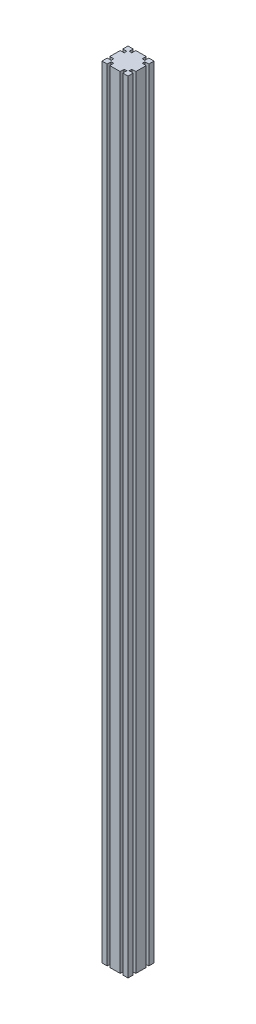
SolidWorks part; units mm, degrees
ref_plane "Front Plane" through (0, 0, 0) normal (0, 0, 1) x (1, 0, 0)
ref_plane "Top Plane" through (0, 0, 0) normal (0, 1, 0) x (1, 0, 0)
ref_plane "Right Plane" through (0, 0, 0) normal (1, 0, 0) x (0, 0, -1)
sketch "Sketch1" plane through (0, 0, 0) normal (0, 1, 0) x (1, 0, 0)
  line L0 (56.6792, 50.48) -> (48.6792, 50.48)
  line L1 (-7.3208, 50.48) -> (8.6792, 50.48)
  line L2 (16.6792, 50.48) -> (48.6792, 50.48)
  line L3 (56.6792, 50.48) -> (72.6792, 50.48)
  line L4 (8.6792, 50.48) -> (16.6792, 50.48)
  line L5 (8.6792, 50.48) -> (8.6792, 38.18)
  line L6 (16.6792, 38.18) -> (8.6792, 38.18)
  line L7 (8.6792, 38.18) -> (8.6792, 50.48)
  line L8 (16.6792, 38.18) -> (16.6792, 50.48)
  line L9 (48.6792, 50.48) -> (48.6792, 38.18)
  line L10 (48.6792, 38.18) -> (56.6792, 38.18)
  line L11 (56.6792, 38.18) -> (56.6792, 50.48)
  line L12 (48.6792, 50.48) -> (48.6792, 38.18)
  line L13 (-7.3208, 50.48) -> (8.6792, 50.48)
  line L14 (72.6792, 50.48) -> (72.6792, 34.48)
  line L15 (72.6792, 34.48) -> (60.3792, 34.48)
  line L17 (60.3792, 34.48) -> (60.3792, 26.48)
  line L19 (60.3792, 26.48) -> (72.6792, 26.48)
  line L21 (72.6792, 26.48) -> (72.6792, -5.52)
  line L22 (72.6792, -5.52) -> (60.3792, -5.52)
  line L23 (60.3792, -5.52) -> (60.3792, -13.52)
  line L24 (60.3792, -13.52) -> (72.6792, -13.52)
  line L28 (72.6792, -13.52) -> (72.6792, -29.52)
  line L29 (72.6792, -29.52) -> (56.6792, -29.52)
  line L30 (56.6792, -29.52) -> (56.6792, -17.22)
  line L31 (56.6792, -17.22) -> (48.6792, -17.22)
  line L32 (48.6792, -17.22) -> (48.6792, -29.52)
  line L33 (48.6792, -29.52) -> (16.6792, -29.52)
  line L34 (16.6792, -29.52) -> (16.6792, -17.22)
  line L35 (16.6792, -17.22) -> (8.6792, -17.22)
  line L36 (8.6792, -17.22) -> (8.6792, -29.52)
  line L37 (8.6792, -29.52) -> (-7.3208, -29.52)
  line L38 (-7.3208, -29.52) -> (-7.3208, -13.52)
  line L39 (-7.3208, -13.52) -> (4.9792, -13.52)
  line L40 (4.9792, -13.52) -> (4.9792, -5.52)
  line L41 (4.9792, -5.52) -> (-7.3208, -5.52)
  line L42 (-7.3208, -5.52) -> (-7.3208, 26.48)
  line L43 (-7.3208, 26.48) -> (4.9792, 26.48)
  line L44 (4.9792, 26.48) -> (4.9792, 34.48)
  line L45 (4.9792, 34.48) -> (-7.3208, 34.48)
  line L46 (-7.3208, 34.48) -> (-7.3208, 50.48)
  point P0 (12.6792, 38.18)
  point P7 (52.6792, 38.18)
  dimension "D1" = 80
  dimension "D2" = 40
  dimension "D3" = 8
  dimension "D4" = 12.3
extrude "Boss-Extrude1" add sketch "Sketch1" along normal blind 2400 contours L46 L45 L44 L43 L42 L41 L40 L39 L38 L37 L36 L35 L34 L33 L32 L31 L30 L29 L28 L24 L23 L22 L21 L19 L17 L15 L14 L3 L11 L10 L9 L2 L8 L6 L5 L1
